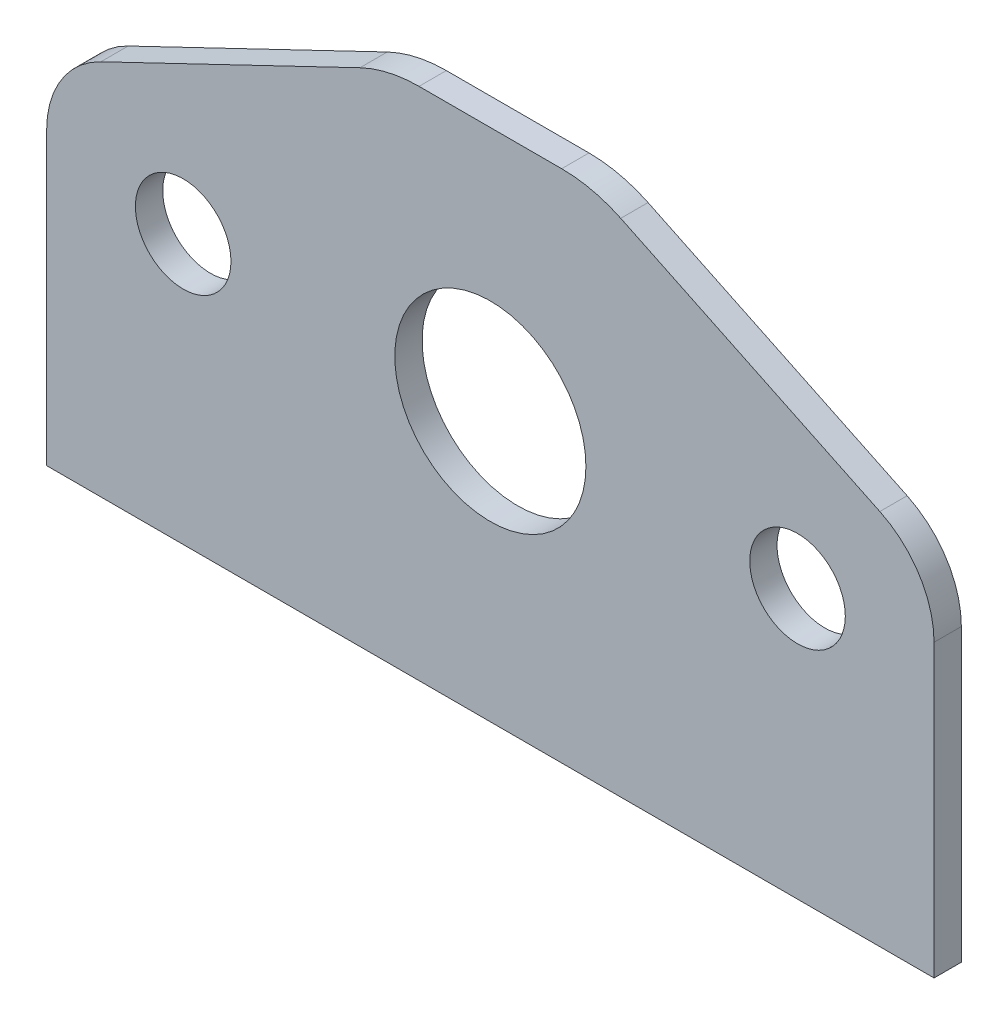
SolidWorks part; units mm, degrees
ref_plane "Front Plane" through (0, 0, 0) normal (0, 0, 1) x (1, 0, 0)
ref_plane "Top Plane" through (0, 0, 0) normal (0, 1, 0) x (1, 0, 0)
ref_plane "Right Plane" through (0, 0, 0) normal (1, 0, 0) x (0, 0, -1)
sketch "Sketch1" plane through (0, 0, 0) normal (0, 0, 1) x (1, 0, 0)
  line L0 (-20.785, 0) -> (20.785, 0) construction
  line L1 (-32.5, -12.7) -> (32.5, -12.7)
  line L2 (0, 7) -> (0, -12.7) construction
  line L3 (-22.5, 7) -> (22.5, 7) construction
  line L4 (-32.5, -12.7) -> (-32.5, 8.5954)
  line L5 (32.5, -12.7) -> (32.5, 8.5954)
  line L6 (-5.2243, 25) -> (5.2243, 25)
  line L7 (-28.5291, 14.906) -> (-9.5516, 24.0152)
  line L8 (28.5291, 14.906) -> (9.5516, 24.0152)
  circle A0 centre (0, 7) radius 5 construction
  circle A1 centre (0, 7) radius 7
  circle A2 centre (-22.5, 7) radius 3.5
  circle A3 centre (22.5, 7) radius 3.5
  arc A4 (28.5291, 14.906) -> (32.5, 8.5954) centre (25.5, 8.5954) cw
  arc A5 (-28.5291, 14.906) -> (-32.5, 8.5954) centre (-25.5, 8.5954) ccw
  arc A6 (9.5516, 24.0152) -> (5.2243, 25) centre (5.2243, 15) ccw
  arc A7 (-9.5516, 24.0152) -> (-5.2243, 25) centre (-5.2243, 15) cw
  point P10 (0, -12.7)
  point P14 (0, 7)
  point P16 (-32.5, 25)
  point P17 (32.5, 25)
  point P24 (32.5, 13)
  point P27 (-32.5, 13)
  point P30 (7.5, 25)
  point P33 (-7.5, 25)
  dimension "D1" = 10
  dimension "D5" = 7
  dimension "D7" = 7
  dimension "D13" = 7
  dimension "D14" = 10
  dimension "D2" = 7
  dimension "D3" = 12.7
  dimension "D4" = 65
  dimension "D6" = 45
  dimension "D8" = 18
  dimension "D9" = 12
  dimension "D10" = 25
  dimension "D11" = 12
  dimension "D12" = 25
extrude "Boss-Extrude1" add sketch "Sketch1" along normal blind 2
